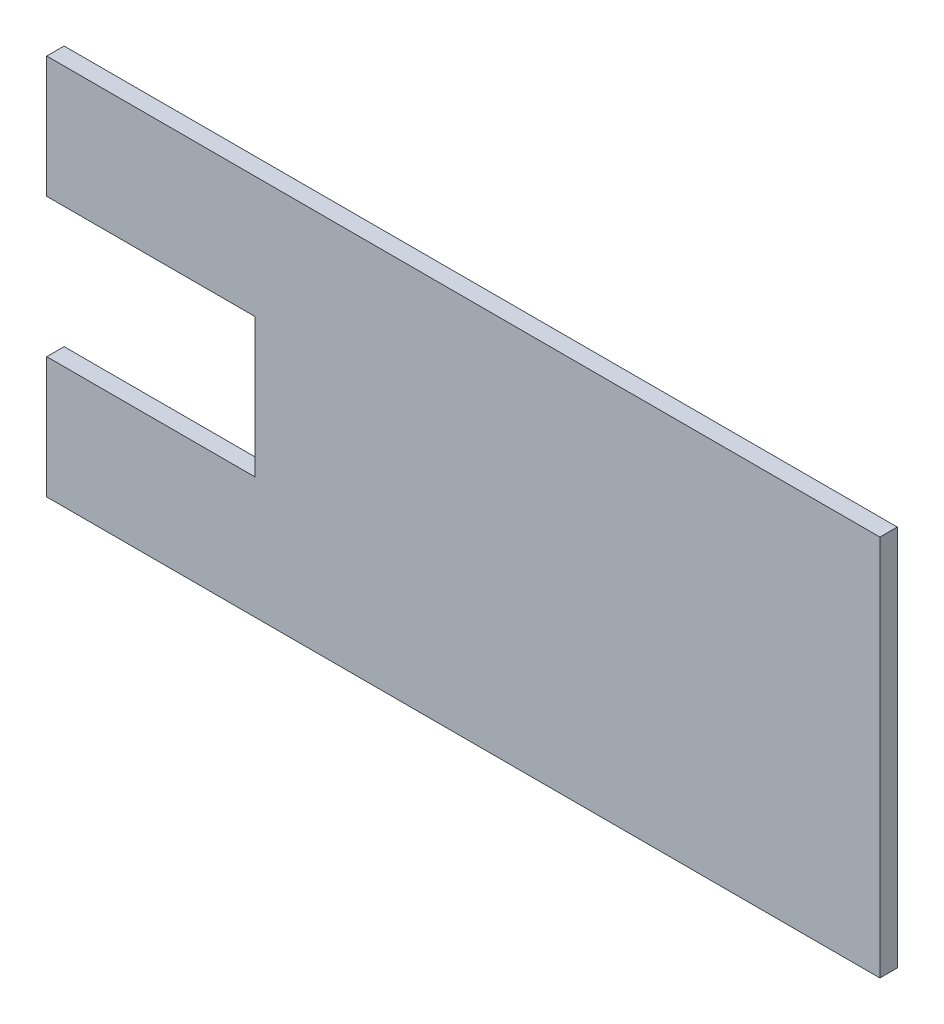
SolidWorks part; units mm, degrees
ref_plane "Front Plane" through (0, 0, 0) normal (0, 0, 1) x (1, 0, 0)
ref_plane "Top Plane" through (0, 0, 0) normal (0, 1, 0) x (1, 0, 0)
ref_plane "Right Plane" through (0, 0, 0) normal (1, 0, 0) x (0, 0, -1)
sketch "Sketch1" plane through (0, 0, 0) normal (0, 0, 1) x (1, 0, 0)
  line L1 (0, 0) -> (152.4, 0)
  line L2 (0, 0) -> (0, 69.85)
  line L3 (0, 69.85) -> (152.4, 69.85)
  line L4 (152.4, 0) -> (152.4, 69.85)
  dimension "D1" = 69.85
  dimension "D2" = 152.4
extrude "Boss-Extrude1" add sketch "Sketch1" along normal blind 3.175
sketch "Sketch2" plane through (0, 0, 3.175) normal (0, 0, 1) x (1, 0, 0)
  line L0 (0, 69.85) -> (0, 0) construction
  line L1 (0, 47.625) -> (38.1, 47.625)
  line L2 (0, 47.625) -> (0, 22.225)
  line L3 (0, 22.225) -> (38.1, 22.225)
  line L4 (38.1, 47.625) -> (38.1, 22.225)
  line L5 (152.4, 0) -> (152.4, 69.85) construction
  point P6 (38.1, 34.925)
  point P7 (152.4, 34.925)
  point P8 (0, 0)
  dimension "D1" = 25.4
  dimension "D2" = 38.1
extrude "Cut-Extrude1" cut sketch "Sketch2" against normal through all
